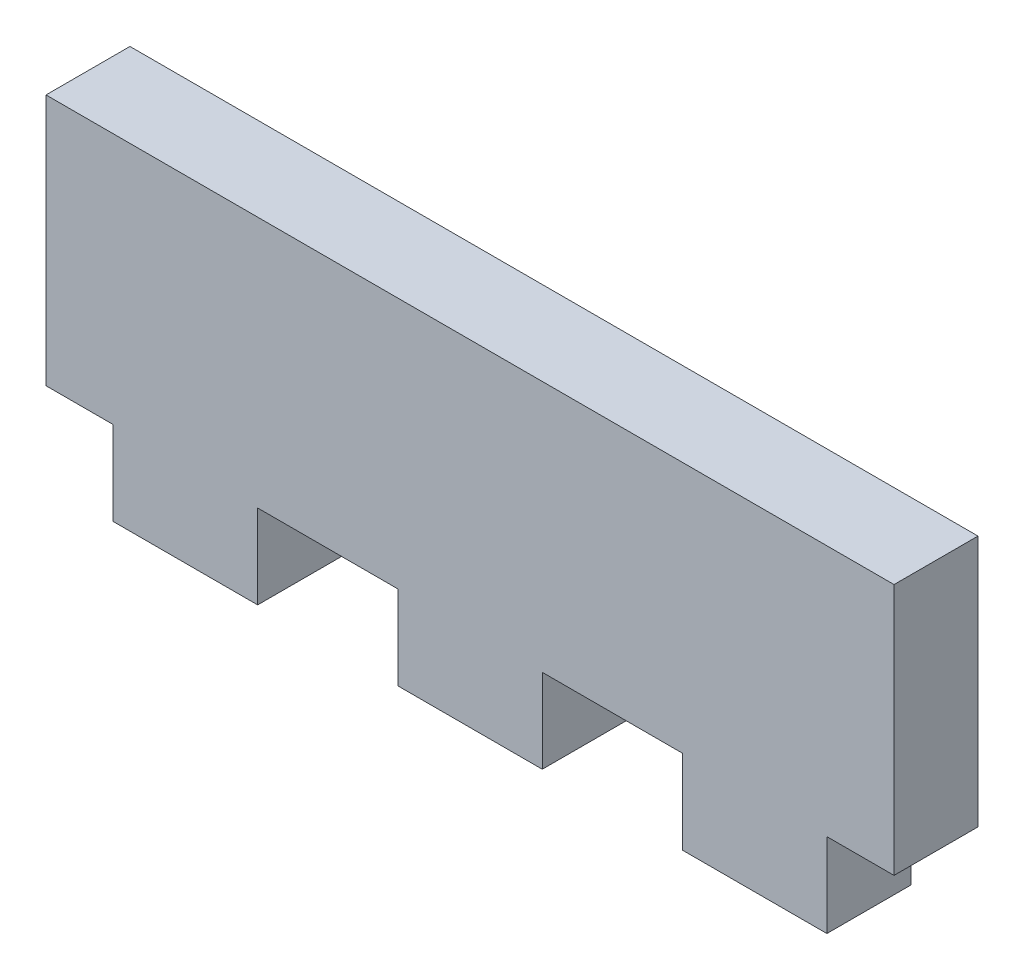
SolidWorks part; units mm, degrees
ref_plane "Front" through (0, 0, 0) normal (0, 0, 1) x (1, 0, 0)
ref_plane "Top" through (0, 0, 0) normal (0, 1, 0) x (1, 0, 0)
ref_plane "Right" through (0, 0, 0) normal (1, 0, 0) x (0, 0, -1)
sketch "Sketch1" plane through (0, 0, 0) normal (0, 0, 1) x (1, 0, 0)
  line L0 (-5.6965, 26.54) -> (-14.2972, 26.54)
  line L1 (-22.644, 26.54) -> (-31.2482, 26.54)
  line L2 (-39.5949, 26.54) -> (-48.1992, 26.54)
  line L3 (-39.5949, 26.54) -> (-39.5949, 31.54)
  line L4 (-31.2482, 26.54) -> (-31.2482, 31.54)
  line L5 (-31.2482, 31.54) -> (-39.5949, 31.54)
  line L6 (-22.644, 26.54) -> (-22.644, 31.54)
  line L7 (-22.644, 31.54) -> (-14.2972, 31.54)
  line L8 (-14.2972, 31.54) -> (-14.2972, 26.54)
  line L9 (-5.6965, 26.54) -> (-5.6965, 31.54)
  line L10 (-5.6965, 31.54) -> (-1.6965, 31.54)
  line L11 (-48.1992, 26.54) -> (-48.1992, 31.54)
  line L12 (-48.1992, 31.54) -> (-52.1992, 31.54)
  line L13 (-1.6965, 31.54) -> (-1.6965, 46.54)
  line L14 (-52.1992, 31.54) -> (-52.1992, 46.54)
  line L15 (-52.1992, 46.54) -> (-1.6965, 46.54)
extrude "Boss-Extrude1" add sketch "Sketch1" along normal blind 5
